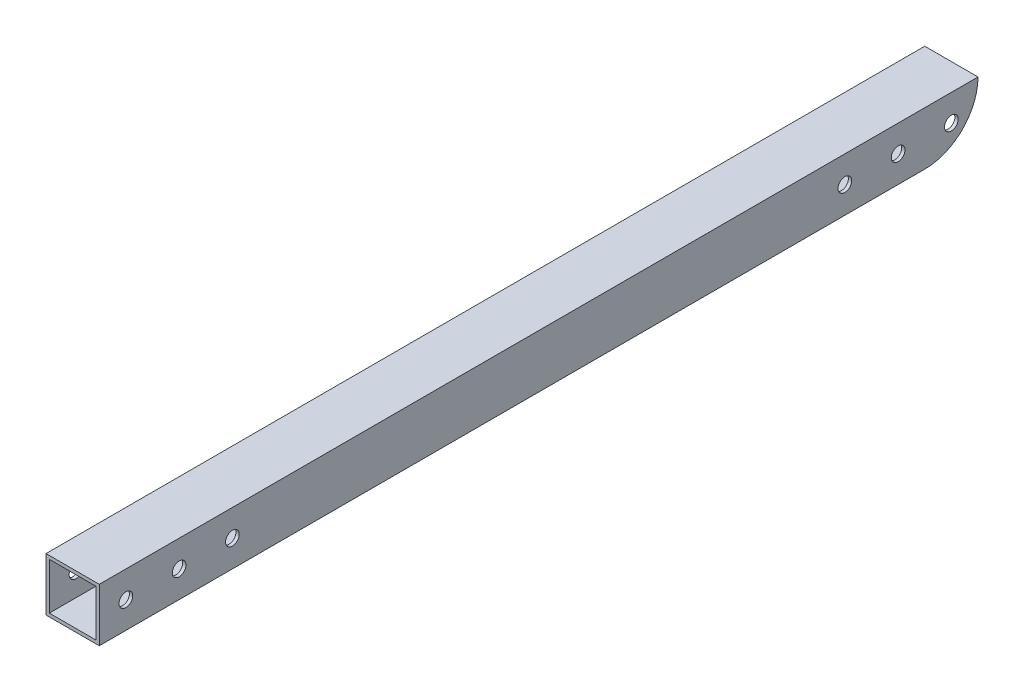
SolidWorks part; units mm, degrees
material "6061 Alloy"
ref_plane "Front Plane" through (0, 0, 0) normal (0, 0, 1) x (1, 0, 0)
ref_plane "Top Plane" through (0, 0, 0) normal (0, 1, 0) x (1, 0, 0)
ref_plane "Right Plane" through (0, 0, 0) normal (1, 0, 0) x (0, 0, -1)
sketch "Sketch1" plane through (0, 0, 0) normal (0, 0, 1) x (1, 0, 0)
  line L1 (0, 0) -> (25.4, 0)
  line L2 (0, 0) -> (0, 25.4)
  line L3 (0, 25.4) -> (25.4, 25.4)
  line L4 (25.4, 0) -> (25.4, 25.4)
  line L5 (1.5875, 23.8125) -> (23.8125, 23.8125)
  line L6 (1.5875, 23.8125) -> (1.5875, 1.5875)
  line L7 (1.5875, 1.5875) -> (23.8125, 1.5875)
  line L8 (23.8125, 23.8125) -> (23.8125, 1.5875)
  dimension "D1" = 25.4
  dimension "D2" = 25.4
  dimension "D3" = 1.5875
  dimension "D4" = 1.5875
  dimension "D5" = 1.5875
  dimension "D6" = 1.5875
extrude "Boss-Extrude1" add sketch "Sketch1" along normal blind 419.1
sketch "Sketch2" plane through (0, 0, 0) normal (-1, 0, 0) x (0, 0, 1)
  line L0 (419.1, 0) -> (0, 0) construction
  line L1 (0, 25.4) -> (0, 0) construction
  line L2 (12.7, 12.7) -> (38.1, 12.7) construction
  line L3 (209.55, 25.4) -> (209.55, 0) construction
  line L4 (419.1, 25.4) -> (0, 25.4) construction
  line L5 (406.4, 12.7) -> (381, 12.7) construction
  circle A0 centre (12.7, 12.7) radius 3.2639
  circle A1 centre (38.1, 12.7) radius 3.2639
  circle A2 centre (63.5, 12.7) radius 3.2639
  circle A3 centre (355.6, 12.7) radius 3.2639
  circle A4 centre (381, 12.7) radius 3.2639
  circle A5 centre (406.4, 12.7) radius 3.2639
  dimension "D3" = 6.5278
  dimension "D1" = 12.7
  dimension "D2" = 12.7
  dimension "D5" = 25.4
  dimension "D4" = 3
extrude "Cut-Extrude1" cut sketch "Sketch2" against normal through all
sketch "Sketch3" plane through (25.4, 0, 0) normal (1, 0, 0) x (0, 0, -1)
  line L0 (0, 25.4) -> (0, 0)
  line L1 (0, 0) -> (0, 25.4) construction
  line L2 (0, 0) -> (-25.4, 0)
  line L3 (-419.1, 0) -> (0, 0) construction
  arc A0 (-25.4, 0) -> (0, 25.4) centre (-25.4, 25.4) ccw
  dimension "D1" = 25.4
extrude "Cut-Extrude2" cut sketch "Sketch3" against normal through all
